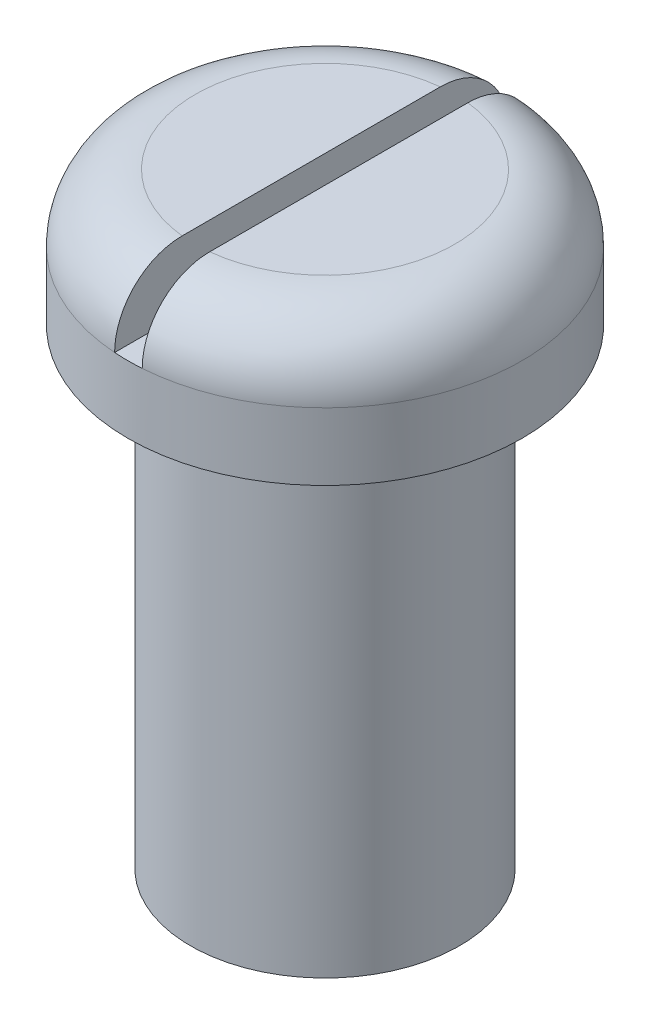
SolidWorks part; units mm, degrees
ref_plane "Front Plane" through (0, 0, 0) normal (0, 0, 1) x (1, 0, 0)
ref_plane "Top Plane" through (0, 0, 0) normal (0, 1, 0) x (1, 0, 0)
ref_plane "Right Plane" through (0, 0, 0) normal (1, 0, 0) x (0, 0, -1)
sketch "Sketch1" plane through (0, 0, 0) normal (0, 0, 1) x (1, 0, 0)
  line L0 (0, 0) -> (0, 9) construction
  line L1 (0, 9) -> (1.93, 9)
  line L2 (2.93, 8) -> (2.93, 7)
  line L3 (2.93, 7) -> (2, 7)
  line L4 (2, 7) -> (2, 0)
  line L5 (2, 0) -> (0, 0)
  line L6 (0, 0) -> (0, 9)
  arc A0 (1.93, 9) -> (2.93, 8) centre (1.93, 8) cw
  point P9 (2.93, 9)
  dimension "D5" = 1
  dimension "D1" = 9
  dimension "D2" = 2
  dimension "D3" = 2.93
  dimension "D4" = 4
revolve "Revolve1" add sketch "Sketch1" angle 360 about L0
sketch "Sketch2" plane through (0, 0, 0) normal (0, 0, 1) x (1, 0, 0)
  line L0 (1.93, 9) -> (-1.93, 9) construction
  line L1 (-0.205, 9) -> (0.205, 9)
  line L2 (-0.205, 9) -> (-0.205, 8)
  line L3 (-0.205, 8) -> (0.205, 8)
  line L4 (0.205, 9) -> (0.205, 8)
  point P6 (0, 9)
  dimension "D1" = 0.41
  dimension "D2" = 1
extrude "Cut-Extrude1" cut sketch "Sketch2" against normal up to next and the other way up to next
